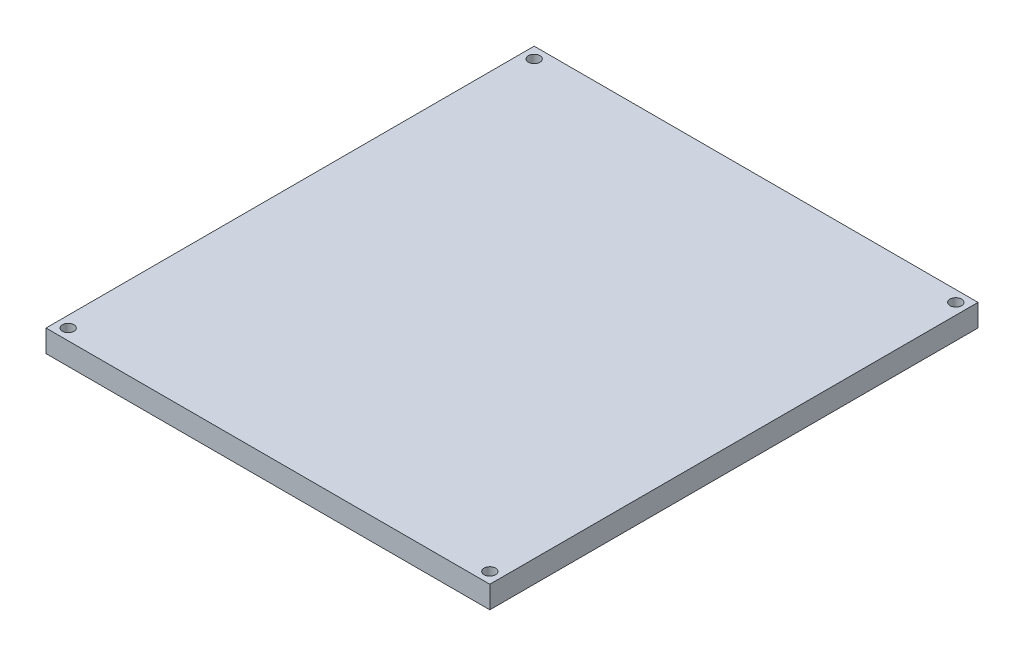
SolidWorks part; units mm, degrees
ref_plane "Front Plane" through (0, 0, 0) normal (0, 0, 1) x (1, 0, 0)
ref_plane "Top Plane" through (0, 0, 0) normal (0, 1, 0) x (1, 0, 0)
ref_plane "Right Plane" through (0, 0, 0) normal (1, 0, 0) x (0, 0, -1)
sketch "Sketch1" plane through (0, 0, 0) normal (0, 1, 0) x (1, 0, 0)
  line L1 (-63.5, -69.85) -> (63.5, -69.85)
  line L2 (-63.5, -69.85) -> (-63.5, 69.85)
  line L3 (-63.5, 69.85) -> (63.5, 69.85)
  line L4 (63.5, -69.85) -> (63.5, 69.85)
  line L5 (-63.5, -69.85) -> (63.5, 69.85) construction
  line L6 (-63.5, 69.85) -> (63.5, -69.85) construction
  point P0 (0, 0)
  dimension "D1" = 127
  dimension "D2" = 139.7
extrude "Boss-Extrude1" add sketch "Sketch1" along normal blind 6.35
sketch "Sketch3" plane through (0, 6.35, 0) normal (0, 1, 0) x (1, 0, 0)
  circle A0 centre (60.325, 66.675) radius 1.65 construction
  circle A1 centre (60.325, -66.675) radius 1.65 construction
  circle A2 centre (-60.325, -66.675) radius 1.65 construction
  circle A3 centre (-60.325, 66.675) radius 1.65 construction
  circle A4 centre (60.325, 66.675) radius 1.65
  circle A5 centre (60.325, -66.675) radius 1.65
  circle A6 centre (-60.325, -66.675) radius 1.65
  circle A7 centre (-60.325, 66.675) radius 1.65
extrude "Cut-Extrude1" cut sketch "Sketch3" against normal through all
